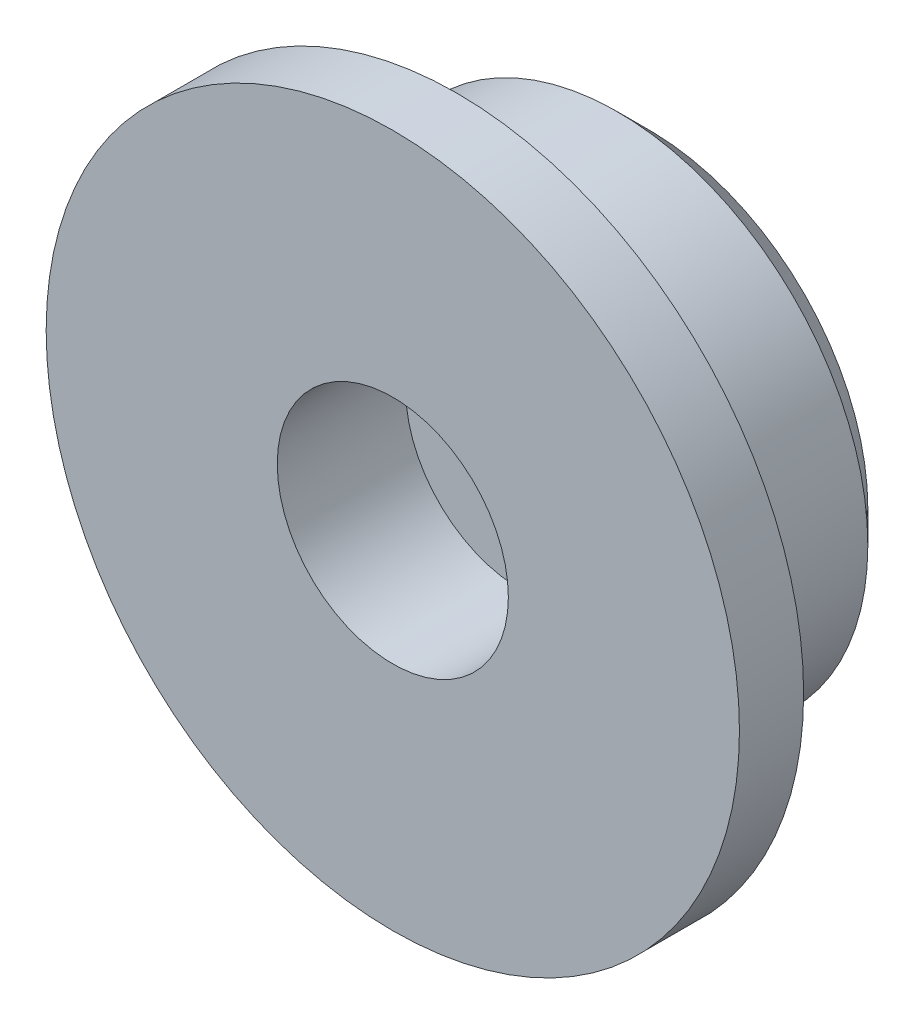
SolidWorks part; units mm, degrees
ref_plane "Спереди" through (0, 0, 0) normal (0, 0, 1) x (1, 0, 0)
ref_plane "Сверху" through (0, 0, 0) normal (0, 1, 0) x (1, 0, 0)
ref_plane "Справа" through (0, 0, 0) normal (1, 0, 0) x (0, 0, -1)
sketch "Эскиз1" plane through (0, 0, 0) normal (0, 0, 1) x (1, 0, 0)
  circle A1 centre (0, 0) radius 3.9
  dimension "D2" = 7.8
extrude "Бобышка-Вытянуть1" add sketch "Эскиз1" along normal blind 3
chamfer "Фаска1" distance 0.5 angle 45 1 edges at (3.9, 0, 0)
sketch "Эскиз4" plane through (0, 0, 3) normal (0, 0, 1) x (1, 0, 0)
  circle A2 centre (0, 0) radius 5.4
  circle A3 centre (0, 0) radius 5.4
  dimension "D1" = 1.5
extrude "Бобышка-Вытянуть2" add sketch "Эскиз4" along normal blind 1
sketch "Эскиз5" plane through (0, 0, 4) normal (0, 0, 1) x (1, 0, 0)
  circle A0 centre (0, 0) radius 1.8
  dimension "D1" = 3.6
extrude "Вырез-Вытянуть2" cut sketch "Эскиз5" against normal blind 2
